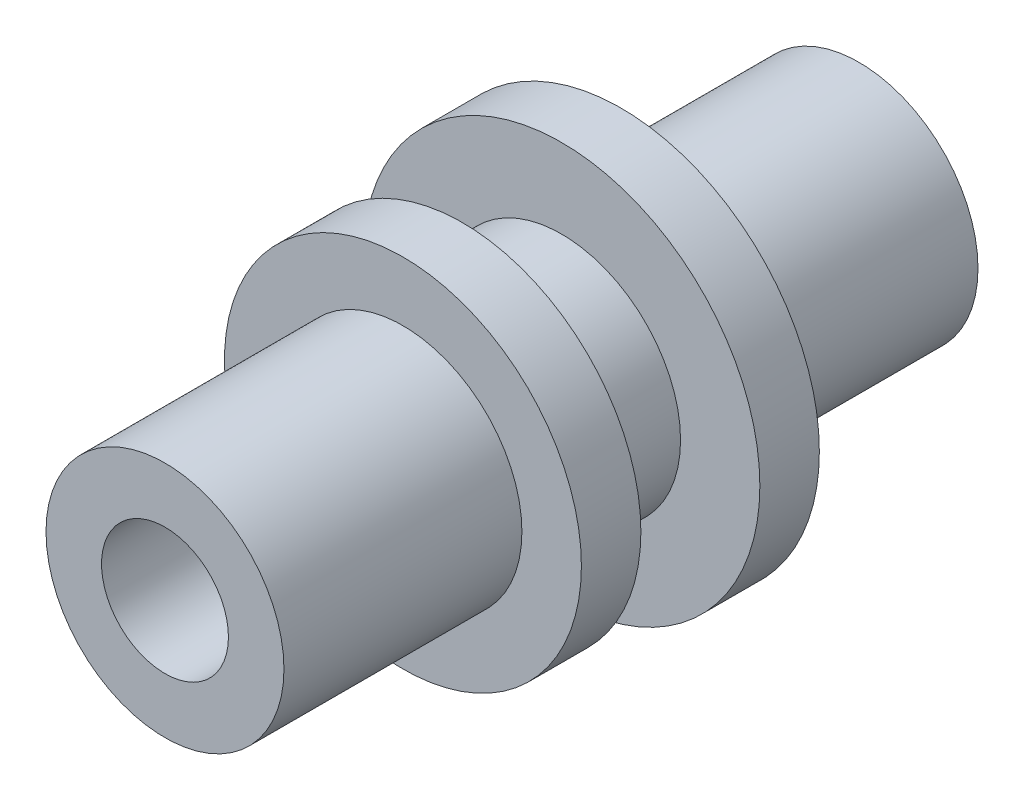
SolidWorks part; units mm, degrees
ref_plane "Front Plane" through (0, 0, 0) normal (0, 0, 1) x (1, 0, 0)
ref_plane "Top Plane" through (0, 0, 0) normal (0, 1, 0) x (1, 0, 0)
ref_plane "Right Plane" through (0, 0, 0) normal (1, 0, 0) x (0, 0, -1)
other "Configuration Table"
sketch "Sketch1" plane through (0, 0, 0) normal (0, 0, 1) x (1, 0, 0)
  circle A0 centre (0, 0) radius 10
  dimension "D1" = 20
extrude "Rear_Flange" add sketch "Sketch1" along normal blind 3 from offset 3
sketch "Sketch2" plane through (0, 0, 0) normal (0, 0, 1) x (1, 0, 0)
  circle A0 centre (0, 0) radius 6
  dimension "D1" = 12
extrude "Through_Body" add sketch "Sketch2" along normal blind 5
sketch "Sketch3" plane through (0, 0, 0) normal (0, 0, 1) x (1, 0, 0)
  circle A0 centre (0, 0) radius 9
  dimension "D1" = 18
extrude "Lock_Nut" add sketch "Sketch3" along normal blind 3 from offset 5
sketch "Sketch4" plane through (0, 0, 0) normal (0, 0, 1) x (1, 0, 0)
  circle A0 centre (0, 0) radius 6
  dimension "D1" = 12
extrude "Inside_Port" add sketch "Sketch4" along normal blind 12 from offset 8
sketch "Sketch5" plane through (0, 0, 0) normal (0, 0, 1) x (1, 0, 0)
  circle A0 centre (0, 0) radius 3.2
  dimension "D1" = 6.4
extrude "Inside_Socket" cut sketch "Sketch5" against normal blind 10 from offset 20
sketch "Sketch6" plane through (0, 0, 0) normal (0, 0, 1) x (1, 0, 0)
  circle A0 centre (0, 0) radius 6
  dimension "D1" = 12
extrude "Outside_Port" add sketch "Sketch6" along normal blind 12 from offset 15
sketch "Sketch7" plane through (0, 0, 0) normal (0, 0, 1) x (1, 0, 0)
  circle A0 centre (0, 0) radius 3.2
  dimension "D1" = 6.4
extrude "Outside_Socket" cut sketch "Sketch7" along normal blind 10 from offset 15
equation "\"Jar_OD\"= 90  'ASSUMED - Part G fallback - jar outer diameter"
equation "\"Jar_H\"= 120  'ASSUMED - Part G fallback - jar height"
equation "\"Pump_L\"= 45  'ASSUMED - Part G fallback"
equation "\"Pump_W\"= 24  'ASSUMED - Part G fallback"
equation "\"Pump_H\"= 33  'ASSUMED - Part G fallback"
equation "\"Pump_Outlet_OD\"= 7.5  'ASSUMED - Part G fallback"
equation "\"Tube_OD\"= 8  'ASSUMED - Part G fallback"
equation "\"Tube_ID\"= 6  'ASSUMED - Part G fallback"
equation "\"TDS_Body_Dia\"= 12  'ASSUMED - Part G fallback"
equation "\"TDS_Wet_Len\"= 45  'ASSUMED - Part G fallback - length in water"
equation "\"DS_Tube_Dia\"= 6  'ASSUMED - Part G fallback"
equation "\"DS_Tube_Len\"= 50  'ASSUMED - Part G fallback"
equation "\"ORP_Body_Dia\"= 12  'ASSUMED - Part G fallback"
equation "\"ORP_Body_Len\"= 150  'ASSUMED - Part G fallback"
equation "\"ORP_Cap_Dia\"= 16  'ASSUMED - Part G fallback"
equation "\"Turb_W\"= 33  'ASSUMED - Part G fallback - head width"
equation "\"Turb_D\"= 28  'ASSUMED - Part G fallback - head depth"
equation "\"Turb_H\"= 30  'ASSUMED - Part G fallback - head height"
equation "\"Turb_Slot_W\"= 10  'ASSUMED - Part G fallback - slot width"
equation "\"Flow_L\"= 62  'ASSUMED - Part G fallback YF-S201"
equation "\"Flow_W\"= 36  'ASSUMED - Part G fallback"
equation "\"Flow_H\"= 35  'ASSUMED - Part G fallback"
equation "\"Thread_G12_OD\"= 20.955  'ASSUMED - Part G fallback thread G1/2 (major diameter)"
equation "\"Valve_L\"= 75  'ASSUMED - Part G fallback"
equation "\"Valve_W\"= 45  'ASSUMED - Part G fallback"
equation "\"Valve_H\"= 60  'ASSUMED - Part G fallback"
equation "\"Tee_L\"= 40  'ASSUMED - Part G fallback - overall length"
equation "\"Tee_Branch_L\"= 25  'ASSUMED - Part G fallback"
equation "\"Tee_OD\"= 12  'ASSUMED - Part G fallback"
equation "\"LED_Board_L\"= 20  'ASSUMED - Part G fallback"
equation "\"LED_Board_W\"= 20  'ASSUMED - Part G fallback - LED at centre"
equation "\"GUVA_L\"= 20  'ASSUMED - Part G fallback"
equation "\"GUVA_W\"= 12  'ASSUMED - Part G fallback - sensor at centre"
equation "\"Reed_L\"= 27  'ASSUMED - Part G fallback MC-38 half"
equation "\"Reed_W\"= 14  'ASSUMED - Part G fallback"
equation "\"Reed_H\"= 8  'ASSUMED - Part G fallback"
equation "\"ESP_L\"= 51  'ASSUMED - Part G fallback"
equation "\"ESP_W\"= 28  'ASSUMED - Part G fallback"
equation "\"TFT_L\"= 58  'ASSUMED - Part G fallback - board"
equation "\"TFT_W\"= 35  'ASSUMED - Part G fallback - board"
equation "\"TFT_Win_L\"= 35  'ASSUMED - Part G fallback - visible window"
equation "\"TFT_Win_W\"= 28  'ASSUMED - Part G fallback - visible window"
equation "\"Relay_L\"= 50  'ASSUMED - Part G fallback"
equation "\"Relay_W\"= 26  'ASSUMED - Part G fallback"
equation "\"Relay_H\"= 19  'ASSUMED - Part G fallback"
equation "\"Mosfet_L\"= 34  'ASSUMED - Part G fallback"
equation "\"Mosfet_W\"= 17  'ASSUMED - Part G fallback"
equation "\"Mosfet_H\"= 12  'ASSUMED - Part G fallback"
equation "\"TDS_Board_L\"= 42  'ASSUMED - Part G fallback"
equation "\"TDS_Board_W\"= 32  'ASSUMED - Part G fallback"
equation "\"Turb_Board_L\"= 38  'ASSUMED - Part G fallback"
equation "\"Turb_Board_W\"= 28  'ASSUMED - Part G fallback"
equation "\"BNC_Thread_Dia\"= 9.5  'ASSUMED - Part G fallback"
equation "\"Plate_L\"= 420  'ASSUMED - Part G fallback"
equation "\"Plate_W\"= 297  'ASSUMED - Part G fallback"
equation "\"Plate_T\"= 6  'ASSUMED - Part G fallback"
equation "\"Booster_L\"= 150  'ASSUMED - Part G fallback - booster pump"
equation "\"Booster_W\"= 95  'ASSUMED - Part G fallback"
equation "\"Booster_H\"= 100  'ASSUMED - Part G fallback"
equation "\"PTube_OD\"= 6.35  'ASSUMED - Part G fallback - product tube 1/4 inch"
equation "\"Qz_Out\"= 12  'ASSUMED - Part G fallback - quartz channel outside square"
equation "\"Qz_Path\"= 10  'ASSUMED - Part G fallback - quartz channel inside light path"
equation "\"Qz_L\"= 40  'ASSUMED - Part G fallback - quartz channel length"
equation "\"LED860_Dia\"= 5  'ASSUMED - Part G fallback - 860 nm LED"
equation "\"BPW_L\"= 5.4  'ASSUMED - Part G fallback - BPW34"
equation "\"BPW_W\"= 4.3  'ASSUMED - Part G fallback - BPW34"
equation "\"Cart_Dia\"= 50  'ASSUMED - Part G fallback - sediment and pre-carbon cartridges"
equation "\"Cart_L\"= 255  'ASSUMED - Part G fallback"
equation "\"UF_Dia\"= 50  'ASSUMED - Part G fallback - UF cartridge"
equation "\"UF_L\"= 260  'ASSUMED - Part G fallback"
equation "\"RO_Dia\"= 62  'ASSUMED - Part G fallback - RO membrane housing"
equation "\"RO_L\"= 300  'ASSUMED - Part G fallback"
equation "\"UVC_Dia\"= 40  'ASSUMED - Part G fallback - UV-C chamber"
equation "\"UVC_L\"= 300  'ASSUMED - Part G fallback"
equation "\"Tank_W\"= 260  'ASSUMED - Part G fallback - storage tank"
equation "\"Tank_D\"= 160  'ASSUMED - Part G fallback"
equation "\"Tank_H\"= 300  'ASSUMED - Part G fallback"
equation "\"Cab_W\"= 400  'ASSUMED - Part G fallback - purifier cabinet"
equation "\"Cab_D\"= 270  'ASSUMED - Part G fallback"
equation "\"Cab_H\"= 560  'ASSUMED - Part G fallback"
equation "\"ORP_Board_L\"= 40  'ASSUMED - Part G fallback - ORP buffer board"
equation "\"ORP_Board_W\"= 30  'ASSUMED - Part G fallback"
equation "\"Opt_Board_L\"= 50  'ASSUMED - Part G fallback - optical front-end board"
equation "\"Opt_Board_W\"= 40  'ASSUMED - Part G fallback"
equation "\"Buck_L\"= 43  'ASSUMED - Part G fallback - 12 V to 5 V buck module"
equation "\"Buck_W\"= 21  'ASSUMED - Part G fallback"
equation "\"Buck_H\"= 14  'ASSUMED - Part G fallback"
equation "\"BB_L\"= 165  'ASSUMED - Part G fallback - breadboard (As_Built_R3 only)"
equation "\"BB_W\"= 55  'ASSUMED - Part G fallback"
equation "\"BB_H\"= 10  'ASSUMED - Part G fallback"
equation "\"Cuv_W\"= 12.5  'ASSUMED - old R3 cuvette (station suppressed in SS4)"
equation "\"Cuv_D\"= 12.5  'ASSUMED - old R3 cuvette (station suppressed in SS4)"
equation "\"Cuv_H\"= 45  'ASSUMED - old R3 cuvette (station suppressed in SS4)"
equation "\"Probe_Clr\"= 0.3  'DESIGN VALUE - Part C rule 3 - printed probe hole = diameter + 0.3"
equation "\"Label_H\"= 0.6  'DESIGN VALUE - Part D - raised label height"
